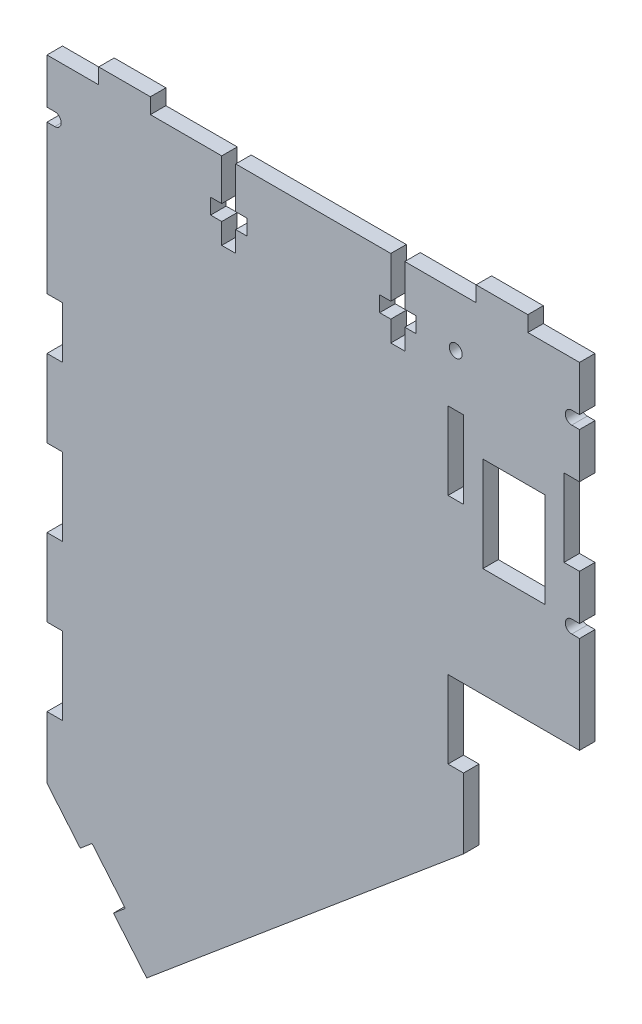
SolidWorks part; units mm, degrees
ref_plane "Front" through (0, 0, 0) normal (0, 0, 1) x (1, 0, 0)
ref_plane "Top" through (0, 0, 0) normal (0, 1, 0) x (1, 0, 0)
ref_plane "Right" through (0, 0, 0) normal (1, 0, 0) x (0, 0, -1)
sketch "Croquis1" plane through (0, 0, 0) normal (0, 0, 1) x (1, 0, 0)
  line L38 (103, 30) -> (103, 21.25)
  line L39 (0, 0) -> (0, -10)
  line L40 (0, -10) -> (3, -10)
  line L41 (3, -10) -> (3, -20)
  line L42 (3, -20) -> (0, -20)
  line L43 (0, -20) -> (0, -35)
  line L44 (0, -35) -> (3, -35)
  line L45 (3, -35) -> (3, -50)
  line L46 (3, -50) -> (0, -50)
  line L47 (0, -50) -> (0, -65)
  line L48 (0, -65) -> (3, -65)
  line L49 (3, -65) -> (3, -80)
  line L50 (3, -80) -> (0, -80)
  line L51 (0, -80) -> (0, -92)
  line L52 (0, -92) -> (6.4279, -99.6604)
  line L53 (6.4279, -99.6604) -> (8.726, -97.7321)
  line L54 (8.726, -97.7321) -> (15.1539, -105.3925)
  line L55 (15.1539, -105.3925) -> (12.8558, -107.3209)
  line L57 (12.8558, -107.3209) -> (19.2836, -114.9813)
  line L59 (19.2836, -114.9813) -> (92.7495, -114.9813) construction
  line L61 (80.5672, -50) -> (80.5672, -63.5583)
  line L62 (80.5672, -63.5583) -> (19.2836, -114.9813)
  line L63 (80.5672, -50) -> (77.5672, -50)
  line L64 (77.5672, -50) -> (77.5672, -35)
  line L66 (80.5672, -5) -> (80.5672, 10)
  line L67 (80.5672, 10) -> (77.5672, 10)
  line L68 (77.5672, 10) -> (77.5672, -5)
  line L69 (77.5672, -5) -> (80.5672, -5)
  line L70 (0, 0) -> (0, 18.75)
  line L71 (0, 30) -> (33.8, 30)
  line L72 (77.5672, -35) -> (103, -35)
  line L73 (1.5, 21.25) -> (0, 21.25)
  line L74 (1.5, 18.75) -> (0, 18.75)
  line L75 (0, 21.25) -> (0, 30)
  line L76 (51.5, 30) -> (51.5, -63.5583) construction
  line L77 (101.5, 18.75) -> (103, 18.75)
  line L78 (101.5, 21.25) -> (103, 21.25)
  line L79 (103, 18.75) -> (103, -13.75)
  line L80 (77.5672, 2.5) -> (-5.015, 2.5) construction
  line L81 (101.5, -16.25) -> (103, -16.25)
  line L82 (101.5, -13.75) -> (103, -13.75)
  line L83 (103, -16.25) -> (103, -35)
  line L84 (51.5, 30) -> (51.5, 36.1054) construction
  line L85 (51.5, 36.1054) -> (103, 36.1054) construction
  line L86 (69.2, 19) -> (71.35, 19)
  line L88 (69.2, 30) -> (69.2, 22)
  line L90 (66.5, 30) -> (66.5, 22)
  line L91 (69.2, 30) -> (66.5, 18.9581) construction
  line L92 (69.2, 18.9581) -> (66.5, 30) construction
  line L93 (64.35, 22) -> (66.5, 22)
  line L94 (64.35, 22) -> (64.35, 19)
  line L95 (64.35, 19) -> (66.5, 19)
  line L96 (71.35, 22) -> (71.35, 19)
  line L97 (64.35, 22) -> (71.35, 19) construction
  line L98 (64.35, 19) -> (71.35, 22) construction
  line L100 (66.5, 19) -> (66.5, 15)
  line L101 (66.5, 15) -> (69.2, 15)
  line L103 (66.5, 18.9581) -> (69.2, 15) construction
  line L104 (66.5, 15) -> (69.2, 18.9581) construction
  line L105 (69.2, 19) -> (69.2, 15)
  line L106 (66.5, 19) -> (66.5, 22) construction
  line L107 (69.2, 22) -> (69.2, 19) construction
  line L108 (66.5, 19) -> (69.2, 19) construction
  line L109 (69.2, 22) -> (71.35, 22)
  line L110 (36.5, 19) -> (33.8, 19) construction
  line L111 (33.8, 22) -> (33.8, 19) construction
  line L112 (36.5, 19) -> (36.5, 22) construction
  line L113 (36.5, 15) -> (33.8, 18.9581) construction
  line L114 (36.5, 18.9581) -> (33.8, 15) construction
  line L115 (38.65, 19) -> (31.65, 22) construction
  line L116 (38.65, 22) -> (31.65, 19) construction
  line L117 (33.8, 18.9581) -> (36.5, 30) construction
  line L118 (33.8, 30) -> (36.5, 18.9581) construction
  line L119 (33.8, 22) -> (31.65, 22)
  line L120 (33.8, 19) -> (33.8, 15)
  line L121 (36.5, 15) -> (33.8, 15)
  line L122 (36.5, 19) -> (36.5, 15)
  line L123 (31.65, 22) -> (31.65, 19)
  line L124 (38.65, 19) -> (36.5, 19)
  line L125 (38.65, 22) -> (38.65, 19)
  line L126 (38.65, 22) -> (36.5, 22)
  line L127 (36.5, 30) -> (36.5, 22)
  line L128 (33.8, 30) -> (33.8, 22)
  line L130 (33.8, 19) -> (31.65, 19)
  line L131 (36.5, 30) -> (66.5, 30)
  line L132 (69.2, 30) -> (103, 30)
  arc A0 (1.5, 18.75) -> (1.5, 21.25) centre (1.5, 20) ccw
  arc A1 (101.5, 18.75) -> (101.5, 21.25) centre (101.5, 20) cw
  arc A2 (101.5, -13.75) -> (101.5, -16.25) centre (101.5, -15) ccw
  circle A3 centre (79.0672, 20) radius 1.25
  point P59 (67.85, 24.4791)
  point P60 (67.85, 20.5)
  point P67 (67.85, 16.9791)
  point P68 (64.35, 20.5)
  point P70 (67.85, 19)
  point P74 (0, 0)
  point P89 (35.15, 16.9791)
  point P90 (35.15, 20.5)
  point P91 (35.15, 24.4791)
  dimension "D16" = 2.5
  dimension "D19" = 2.5
  dimension "D2" = 103
  dimension "D3" = 13.5583
  dimension "D4" = 10
  dimension "D5" = 15
  dimension "D6" = 3
  dimension "D7" = 30
  dimension "D8" = 20
  dimension "D9" = 3
  dimension "D10" = 40
  dimension "D11" = 10
  dimension "D12" = 80
  dimension "D13" = 3
  dimension "D14" = 3
  dimension "D15" = 15
  dimension "D17" = 10
  dimension "D18" = 1.5
  dimension "D20" = 15
  dimension "D21" = 8
  dimension "D22" = 15
  dimension "D23" = 2.7
  dimension "D24" = 7
  dimension "D25" = 3
extrude "Saliente-Extruir1" add sketch "Croquis1" along normal blind 3
sketch "Croquis2" plane through (103, 0, 0) normal (1, 0, 0) x (0, 0, -1)
  line L0 (0, 30) -> (0, 21.25) construction
  line L1 (0, 10) -> (-3, 10)
  line L2 (0, 10) -> (0, -5)
  line L3 (0, -5) -> (-3, -5)
  line L4 (-3, 10) -> (-3, -5)
  line L5 (0, 10) -> (-3, -5) construction
  line L6 (0, -5) -> (-3, 10) construction
  line L7 (-3, 30) -> (-3, 21.25) construction
  point P4 (-1.5, 2.5)
  dimension "D1" = 20
  dimension "D2" = 15
extrude "Cortar-Extruir1" cut sketch "Croquis2" against normal blind 3
sketch "Croquis3" plane through (0, 0, 3) normal (0, 0, 1) x (1, 0, 0)
  line L0 (0, 30) -> (33.8, 30) construction
  line L1 (10, 30) -> (20, 30)
  line L2 (10, 30) -> (10, 33)
  line L3 (10, 33) -> (20, 33)
  line L4 (20, 30) -> (20, 33)
  line L5 (10, 30) -> (20, 33) construction
  line L6 (10, 33) -> (20, 30) construction
  line L7 (69.2, 30) -> (103, 30) construction
  line L8 (93, 30) -> (83, 30)
  line L9 (93, 30) -> (93, 33)
  line L10 (93, 33) -> (83, 33)
  line L11 (83, 30) -> (83, 33)
  line L12 (93, 30) -> (83, 33) construction
  line L13 (93, 33) -> (83, 30) construction
  line L14 (103, 30) -> (103, 21.25) construction
  line L15 (0, 21.25) -> (0, 30) construction
  point P4 (15, 31.5)
  point P11 (88, 31.5)
  dimension "D1" = 10
  dimension "D2" = 10
  dimension "D3" = 3
  dimension "D4" = 3
  dimension "D5" = 10
  dimension "D6" = 10
extrude "Saliente-Extruir2" add sketch "Croquis3" against normal blind 3
sketch "Croquis4" plane through (0, 0, 3) normal (0, 0, 1) x (1, 0, 0)
  line L0 (84.3041, -16.9277) -> (84.3041, -21.9277) construction
  line L1 (96.3041, 4.4723) -> (84.3041, 4.4723)
  line L2 (96.3041, 4.4723) -> (96.3041, -13.8916)
  line L3 (96.3041, -13.8916) -> (84.3041, -13.8916)
  line L4 (84.3041, 4.4723) -> (84.3041, -13.8916)
  line L5 (96.3041, 4.4723) -> (84.3041, -13.8916) construction
  line L6 (96.3041, -13.8916) -> (84.3041, 4.4723) construction
  point P4 (90.3041, -4.7096)
extrude "Cortar-Extruir2" cut sketch "Croquis4" against normal blind 3
